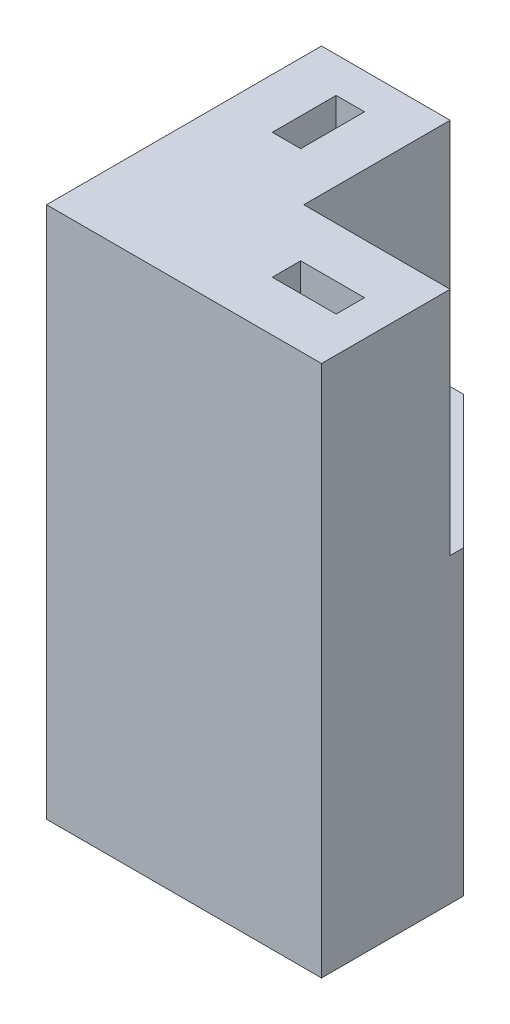
SolidWorks part; units mm, degrees
ref_plane "Front Plane" through (0, 0, 0) normal (0, 0, 1) x (1, 0, 0)
ref_plane "Top Plane" through (0, 0, 0) normal (0, 1, 0) x (1, 0, 0)
ref_plane "Right Plane" through (0, 0, 0) normal (1, 0, 0) x (0, 0, -1)
sketch "Sketch3" plane through (0, 0, 0) normal (0, 1, 0) x (1, 0, 0)
  line L1 (-9.8425, -9.8425) -> (9.8425, -9.8425)
  line L2 (-9.8425, -9.8425) -> (-9.8425, 9.8425)
  line L3 (-9.8425, 9.8425) -> (9.8425, 9.8425)
  line L4 (9.8425, -9.8425) -> (9.8425, 9.8425)
  line L5 (-9.8425, -9.8425) -> (9.8425, 9.8425) construction
  line L6 (-9.8425, 9.8425) -> (9.8425, -9.8425) construction
  point P0 (0, 0)
  dimension "D1" = 19.685
  dimension "D2" = 19.685
extrude "Boss-Extrude2" add sketch "Sketch3" along normal blind 38.1
sketch "Sketch4" plane through (0, 38.1, 0) normal (0, 1, 0) x (1, 0, 0)
  line L0 (9.8425, 9.8425) -> (0, 9.8425)
  line L1 (9.8425, 9.8425) -> (-9.8425, 9.8425) construction
  line L2 (0, 9.8425) -> (0, 0)
  line L3 (0, 0) -> (9.8425, 0)
  line L4 (9.8425, -9.8425) -> (9.8425, 9.8425) construction
  line L5 (9.8425, 0) -> (9.8425, 9.8425)
sketch "Sketch5" plane through (0, 0, 0) normal (0, -1, 0) x (1, 0, 0)
  line L1 (0, 0) -> (-9.8425, 9.8425) construction
  circle A1 centre (-4.9212, 4.9213) radius 2.54
  dimension "D1" = 5.08
extrude "Cut-Extrude2" cut sketch "Sketch5" against normal blind 5.715
sketch "Sketch6" plane through (0, 38.1, 0) normal (0, 1, 0) x (1, 0, 0)
  line L0 (9.8425, -0.635) -> (-0.635, -0.635)
  line L1 (9.8425, -9.8425) -> (9.8425, 9.8425) construction
  line L2 (-0.635, -0.635) -> (-0.635, 9.8425)
  line L3 (9.8425, 9.8425) -> (-9.8425, 9.8425) construction
  line L4 (9.8425, 9.8425) -> (0, 9.8425) construction
  line L5 (-0.635, 9.8425) -> (9.8425, 9.8425)
  line L6 (9.8425, 9.8425) -> (9.8425, -0.635)
  dimension "D1" = 10.4775
  dimension "D2" = 10.4775
extrude "Cut-Extrude3" cut sketch "Sketch6" against normal blind 16.51
sketch "Sketch7" plane through (0, 38.1, 0) normal (0, 1, 0) x (1, 0, 0)
  line L0 (-5.2387, 9.8425) -> (-5.2387, -9.8425) construction
  line L1 (-0.635, 9.8425) -> (-9.8425, 9.8425) construction
  line L2 (-9.8425, -9.8425) -> (9.8425, -9.8425) construction
  line L3 (9.8425, -5.2387) -> (-9.8425, -5.2388) construction
  line L4 (9.8425, -9.8425) -> (9.8425, -0.635) construction
  line L5 (-9.8425, 9.8425) -> (-9.8425, -9.8425) construction
  line L7 (-6.2547, 2.7305) -> (-4.2227, 2.7305)
  line L8 (-6.2547, 2.7305) -> (-6.2547, 7.3025)
  line L9 (-6.2547, 7.3025) -> (-4.2227, 7.3025)
  line L10 (-4.2227, 2.7305) -> (-4.2227, 7.3025)
  line L11 (-6.2547, 2.7305) -> (-4.2227, 7.3025) construction
  line L12 (-6.2547, 7.3025) -> (-4.2227, 2.7305) construction
  line L13 (2.7305, -6.2547) -> (7.3025, -6.2547)
  line L14 (2.7305, -6.2547) -> (2.7305, -4.2227)
  line L15 (2.7305, -4.2227) -> (7.3025, -4.2227)
  line L16 (7.3025, -6.2547) -> (7.3025, -4.2227)
  line L17 (2.7305, -6.2547) -> (7.3025, -4.2227) construction
  line L18 (2.7305, -4.2227) -> (7.3025, -6.2547) construction
  point P12 (-5.2387, 5.0165)
  point P17 (5.0165, -5.2388)
  dimension "D1" = 2.032
  dimension "D2" = 4.572
  dimension "D3" = 2.54
  dimension "D6" = 2.54
extrude "Cut-Extrude4" cut sketch "Sketch7" against normal blind 5.08
chamfer "Chamfer1" distance 9.525 angle 45 1 edges at (9.8425, 10.795, -9.8425)
